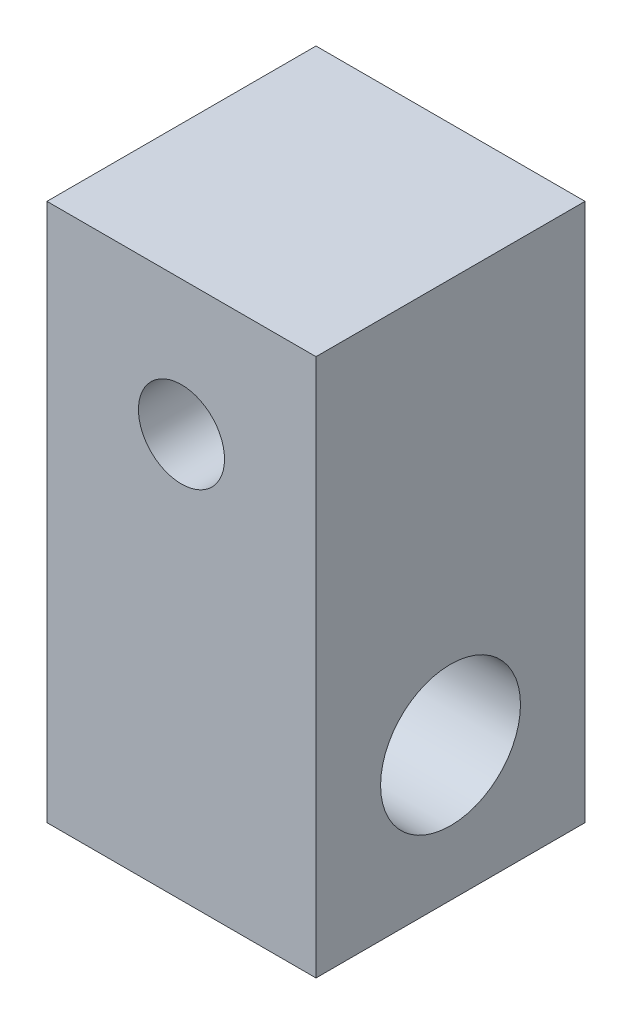
SolidWorks part; units mm, degrees
ref_plane "正面" through (0, 0, 0) normal (0, 0, 1) x (1, 0, 0)
ref_plane "平面" through (0, 0, 0) normal (0, 1, 0) x (1, 0, 0)
ref_plane "右側面" through (0, 0, 0) normal (1, 0, 0) x (0, 0, -1)
sketch "ｽｹｯﾁ1" plane through (0, 0, 0) normal (0, 0, 1) x (1, 0, 0)
  line L1 (0, 20) -> (10, 20)
  line L2 (0, 20) -> (0, 0)
  line L3 (0, 0) -> (10, 0)
  line L4 (10, 20) -> (10, 0)
  dimension "D1" = 20
  dimension "D2" = 10
extrude "ﾎﾞｽ - 押し出し1" add sketch "ｽｹｯﾁ1" along normal blind 10
sketch "ｽｹｯﾁ2" plane through (10, 0, 0) normal (1, 0, 0) x (0, 0, -1)
  line L0 (-10, 20) -> (0, 20) construction
  line L2 (-10, 0) -> (0, 0) construction
  circle A0 centre (-5, 5) radius 2.6
  point P2 (0, 0)
  point P5 (-5, 20)
  dimension "D1" = 5.2
  dimension "D2" = 5
extrude "ｶｯﾄ - 押し出し1" cut sketch "ｽｹｯﾁ2" against normal through all
sketch "ｽｹｯﾁ3" plane through (0, 0, 10) normal (0, 0, 1) x (1, 0, 0)
  line L0 (10, 20) -> (0, 20) construction
  circle A0 centre (5, 15) radius 1.6
  point P4 (5, 20)
  dimension "D2" = 3.2
  dimension "D1" = 5
extrude "ｶｯﾄ - 押し出し2" cut sketch "ｽｹｯﾁ3" against normal blind 10
